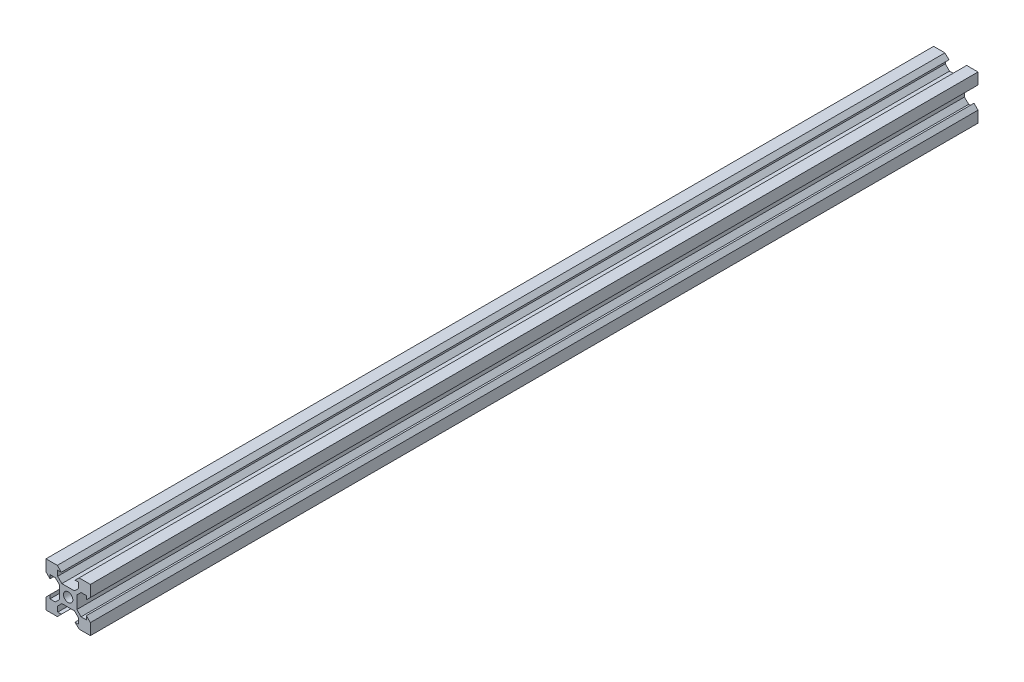
SolidWorks part; units mm, degrees
material "6063-T5"
ref_plane "Front Plane" through (0, 0, 0) normal (0, 0, 1) x (1, 0, 0)
ref_plane "Top Plane" through (0, 0, 0) normal (0, 1, 0) x (1, 0, 0)
ref_plane "Right Plane" through (0, 0, 0) normal (1, 0, 0) x (0, 0, -1)
sketch "Sketch1" plane through (0, 0, 0) normal (0, 0, 1) x (1, 0, 0)
  line L0 (-3.9007, -2.84) -> (-3.9007, 2.84)
  line L1 (-3.9007, 2.84) -> (-5.8007, 4.74)
  line L2 (-5.8007, 4.74) -> (-8.2, 4.74)
  line L3 (-8.2, 4.74) -> (-8.2, 3.1)
  line L4 (-10, 10) -> (-1.4849, 1.4849) construction
  line L5 (0, 3.9007) -> (-2.84, 3.9007)
  line L6 (-2.84, 3.9007) -> (-4.74, 5.8007)
  line L7 (-4.74, 8.2) -> (-3.1, 8.2)
  line L8 (-4.74, 5.8007) -> (-4.74, 8.2)
  line L9 (-3.1, 8.2) -> (-4.9, 10)
  line L10 (-4.9, 10) -> (-10, 10)
  line L11 (-10, 10) -> (-10, 4.9)
  line L12 (-8.2, 3.1) -> (-10, 4.9)
  line L13 (0, 3.9007) -> (0, -3.9007) construction
  line L14 (10, 10) -> (1.4849, 1.4849) construction
  line L15 (8.2, 3.1) -> (10, 4.9)
  line L16 (10, 10) -> (10, 4.9)
  line L17 (4.9, 10) -> (10, 10)
  line L18 (3.1, 8.2) -> (4.9, 10)
  line L19 (4.74, 5.8007) -> (4.74, 8.2)
  line L20 (4.74, 8.2) -> (3.1, 8.2)
  line L21 (2.84, 3.9007) -> (4.74, 5.8007)
  line L22 (8.2, 4.74) -> (8.2, 3.1)
  line L23 (5.8007, 4.74) -> (8.2, 4.74)
  line L24 (3.9007, 2.84) -> (5.8007, 4.74)
  line L25 (2.84, 3.9007) -> (0, 3.9007)
  line L26 (3.9007, 2.84) -> (3.9007, -2.84)
  line L27 (-3.9007, 0) -> (3.9007, 0) construction
  line L28 (10, -10) -> (1.4849, -1.4849) construction
  line L29 (-10, -10) -> (-1.4849, -1.4849) construction
  line L30 (2.84, -3.9007) -> (0, -3.9007)
  line L31 (3.9007, -2.84) -> (5.8007, -4.74)
  line L32 (5.8007, -4.74) -> (8.2, -4.74)
  line L33 (8.2, -4.74) -> (8.2, -3.1)
  line L34 (2.84, -3.9007) -> (4.74, -5.8007)
  line L35 (4.74, -8.2) -> (3.1, -8.2)
  line L36 (4.74, -5.8007) -> (4.74, -8.2)
  line L37 (3.1, -8.2) -> (4.9, -10)
  line L38 (4.9, -10) -> (10, -10)
  line L39 (10, -10) -> (10, -4.9)
  line L40 (8.2, -3.1) -> (10, -4.9)
  line L41 (-8.2, -3.1) -> (-10, -4.9)
  line L42 (-10, -10) -> (-10, -4.9)
  line L43 (-4.9, -10) -> (-10, -10)
  line L44 (-3.1, -8.2) -> (-4.9, -10)
  line L45 (-4.74, -5.8007) -> (-4.74, -8.2)
  line L46 (-4.74, -8.2) -> (-3.1, -8.2)
  line L47 (-2.84, -3.9007) -> (-4.74, -5.8007)
  line L48 (0, -3.9007) -> (-2.84, -3.9007)
  line L49 (-8.2, -4.74) -> (-8.2, -3.1)
  line L50 (-5.8007, -4.74) -> (-8.2, -4.74)
  line L51 (-3.9007, -2.84) -> (-5.8007, -4.74)
  circle A0 centre (0, 0) radius 2.1
  point P10 (-4.8507, 3.79)
  dimension "D1" = 4.2
  dimension "D2" = 5.68
  dimension "D3" = 1.64
  dimension "D4" = 6.2
  dimension "D5" = 0.75
  dimension "D6" = 10
  dimension "D7" = 90
  dimension "D8" = 1.8
extrude "Boss-Extrude1" add sketch "Sketch1" along normal mid plane 400
